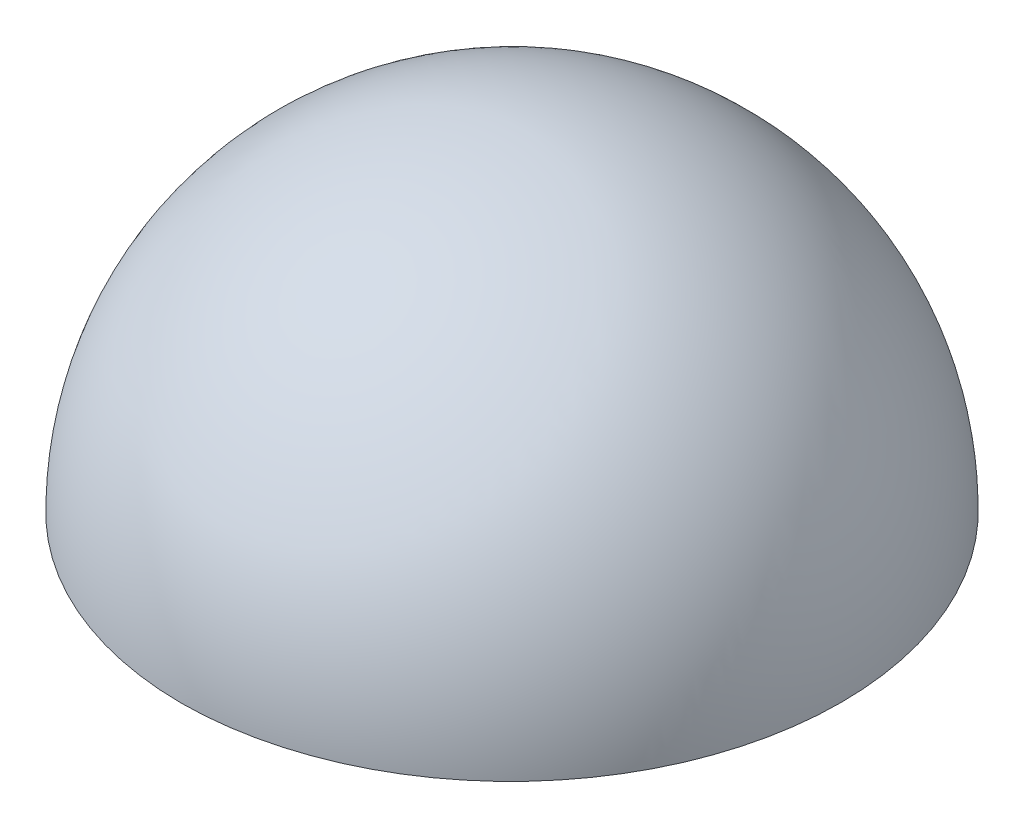
SolidWorks part; units mm, degrees
ref_plane "Front Plane" through (0, 0, 0) normal (0, 0, 1) x (1, 0, 0)
ref_plane "Top Plane" through (0, 0, 0) normal (0, 1, 0) x (1, 0, 0)
ref_plane "Right Plane" through (0, 0, 0) normal (1, 0, 0) x (0, 0, -1)
sketch "Sketch1" plane through (0, 0, 0) normal (0, 1, 0) x (1, 0, 0)
  line L0 (0.0771, 37.2219) -> (0.0771, 35.2808)
  line L1 (0.0771, -34.7186) -> (0.0771, -36.7774)
  arc A0 (0.0771, -36.7774) -> (0.0771, 37.2219) centre (-0.0782, 0.2223) ccw
  arc A1 (0.0771, -34.7186) -> (0.0771, 35.2808) centre (-0.0782, 0.2811) ccw
  point P7 (0.0771, 0.2223)
revolve "Revolve3" add sketch "Sketch1" angle 180 about L0
